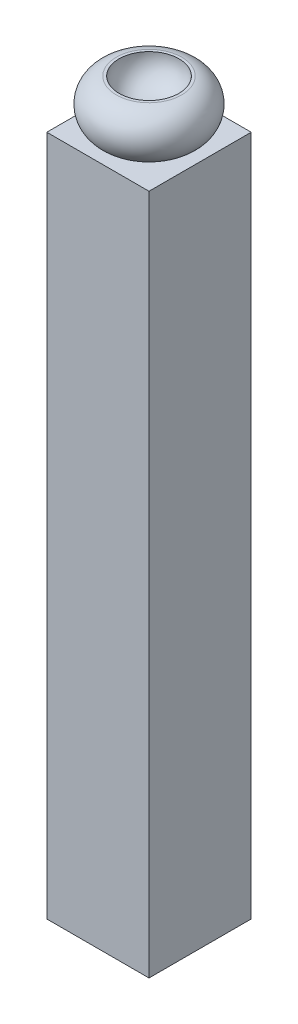
SolidWorks part; units mm, degrees
material "PLA"
ref_plane "Front Plane" through (0, 0, 0) normal (0, 0, 1) x (1, 0, 0)
ref_plane "Top Plane" through (0, 0, 0) normal (0, 1, 0) x (1, 0, 0)
ref_plane "Right Plane" through (0, 0, 0) normal (1, 0, 0) x (0, 0, -1)
sketch "Sketch2" plane through (0, 0, 0) normal (0, 0, 1) x (1, 0, 0)
  line L0 (0, 3.6367) -> (0, 12.7)
  line L1 (0, -55) -> (0, 55) construction
  line L2 (0, 12.7) -> (6.096, 12.7)
  line L6 (4.9472, 3.6367) -> (0, 3.6367)
  arc A0 (6.096, 12.7) -> (4.9472, 3.6367) centre (5.3293, 8.1927) cw
  arc A1 (5.588, 12.7) -> (0, 8.1684) centre (1.1434, 12.4695) cw
  point P11 (5.588, 12.7)
  point P12 (0, 7.6604)
  point P13 (0, 8.1684)
  dimension "D5" = 4.572
  dimension "D8" = 4.4505
  dimension "D2" = 6.096
  dimension "D6" = 0.508
  dimension "D7" = 0.508
revolve "Revolve2" add sketch "Sketch2" angle 360 about L0
sketch "Sketch4" plane through (0, 3.6367, 0) normal (0, -1, 0) x (1, 0, 0)
  line L1 (-9.525, 9.525) -> (9.525, 9.525)
  line L2 (-9.525, 9.525) -> (-9.525, -9.525)
  line L3 (-9.525, -9.525) -> (9.525, -9.525)
  line L4 (9.525, 9.525) -> (9.525, -9.525)
  line L5 (-9.525, 9.525) -> (9.525, -9.525) construction
  line L6 (-9.525, -9.525) -> (9.525, 9.525) construction
  point P0 (0, 0)
  dimension "D1" = 19.05
  dimension "D2" = 19.05
extrude "Boss-Extrude1" add sketch "Sketch4" along normal blind 127
ref_plane "Plane2" through (0, 4.9067, 0) normal (0, 1, 0) x (1, 0, 0)
sketch "Sketch5" plane through (0, 4.9067, 0) normal (0, 1, 0) x (1, 0, 0)
  point P0 (0, 0)
